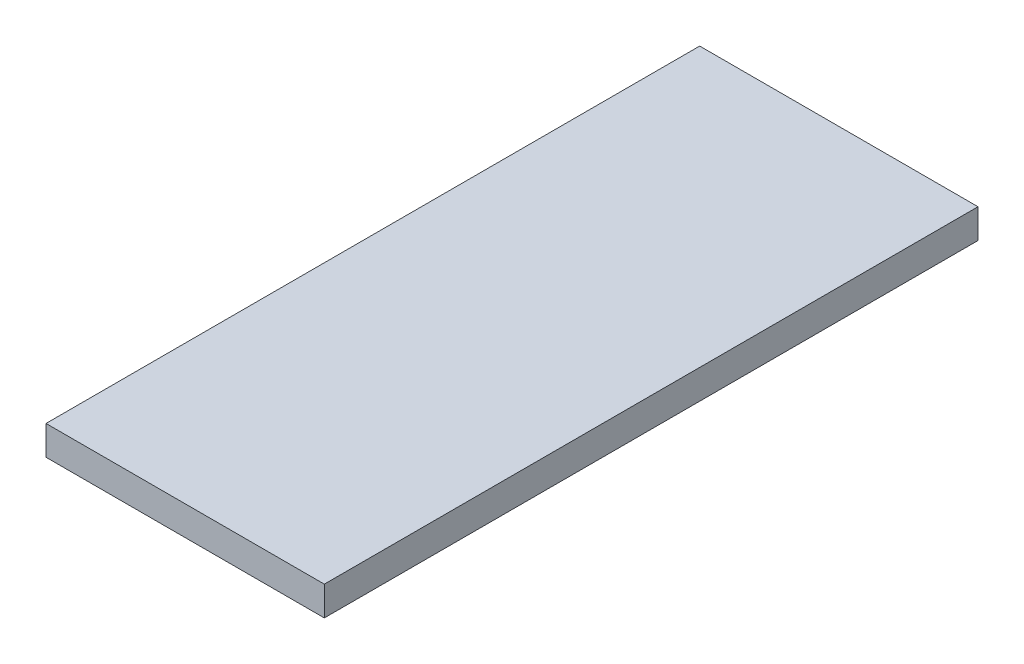
SolidWorks part; units mm, degrees
ref_plane "前视基准面" through (0, 0, 0) normal (0, 0, 1) x (1, 0, 0)
ref_plane "上视基准面" through (0, 0, 0) normal (0, 1, 0) x (1, 0, 0)
ref_plane "右视基准面" through (0, 0, 0) normal (1, 0, 0) x (0, 0, -1)
sketch "草图1" plane through (0, 0, 0) normal (0, 1, 0) x (1, 0, 0)
  line L0 (0, 34.8441) -> (0, -27.9202) construction
  line L1 (-7.6, 17.85) -> (7.6, 17.85)
  line L2 (-7.6, 17.85) -> (-7.6, -17.85)
  line L3 (-7.6, -17.85) -> (7.6, -17.85)
  line L4 (7.6, 17.85) -> (7.6, -17.85)
  line L5 (-31.6913, 0) -> (31.7597, 0) construction
  dimension "D1" = 15.2
  dimension "D2" = 35.7
extrude "凸台-拉伸1" add sketch "草图1" along normal blind 1.6
